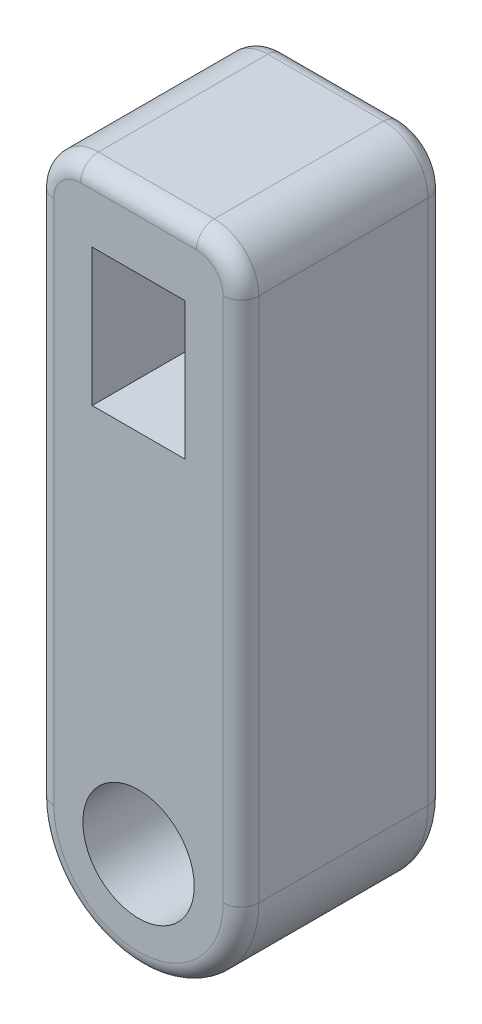
SolidWorks part; units mm, degrees
ref_plane "Front Plane" through (0, 0, 0) normal (0, 0, 1) x (1, 0, 0)
ref_plane "Top Plane" through (0, 0, 0) normal (0, 1, 0) x (1, 0, 0)
ref_plane "Right Plane" through (0, 0, 0) normal (1, 0, 0) x (0, 0, -1)
sketch "Sketch1" plane through (0, 0, 0) normal (0, 0, 1) x (1, 0, 0)
  line L0 (0, -64) -> (0, 64) construction
  line L1 (-11.5, -12.5) -> (11.5, -12.5)
  line L2 (-11.5, -12.5) -> (-11.5, 64)
  line L3 (-11.5, 64) -> (11.5, 64)
  line L4 (11.5, -12.5) -> (11.5, 64)
  line L5 (-11.5, -12.5) -> (11.5, 64) construction
  line L6 (-11.5, 64) -> (11.5, -12.5) construction
  line L7 (-5.2, 41) -> (5.2, 41)
  line L8 (-5.2, 41) -> (-5.2, 56.4)
  line L9 (-5.2, 56.4) -> (5.2, 56.4)
  line L10 (5.2, 41) -> (5.2, 56.4)
  line L11 (-5.2, 41) -> (5.2, 56.4) construction
  line L12 (-5.2, 56.4) -> (5.2, 41) construction
  circle A0 centre (0, 0) radius 6.25
  circle A1 centre (0, 0) radius 11.5
  point P3 (0, 25.75)
  point P8 (0, 48.7)
  point P15 (0, 0)
  dimension "D1" = 12.5
  dimension "D2" = 23
  dimension "D3" = 41
  dimension "D4" = 23
  dimension "D5" = 10.4
  dimension "D6" = 6.3
  dimension "D7" = 15.4
  dimension "D8" = 12.5
  dimension "D9" = 7.6
extrude "Boss-Extrude1" add sketch "Sketch1" along normal blind 23 contours A1 L4 L3 L2 L10 L7 L8 L9 | A1 A0
chamfer "Chamfer2" distance 1 angle 70 4 edges at (5.2, 48.7, 0) (0, 41, 0) (-5.2, 48.7, 0) (0, 56.4, 0)
fillet "Fillet2" radius 5 2 edges at (-11.5, 64, 11.5) (11.5, 64, 11.5)
fillet "Fillet3" radius 2 12 edges at (0, -11.5, 0) (11.5, 29.5, 0) (10.0355, 62.5355, 0) (0, 64, 0) (-10.0355, 62.5355, 0) (0, -11.5, 23) (11.5, 29.5, 23) (10.0355, 62.5355, 23) (0, 64, 23) (-10.0355, 62.5355, 23) (-11.5, 29.5, 0) (-11.5, 29.5, 23)
